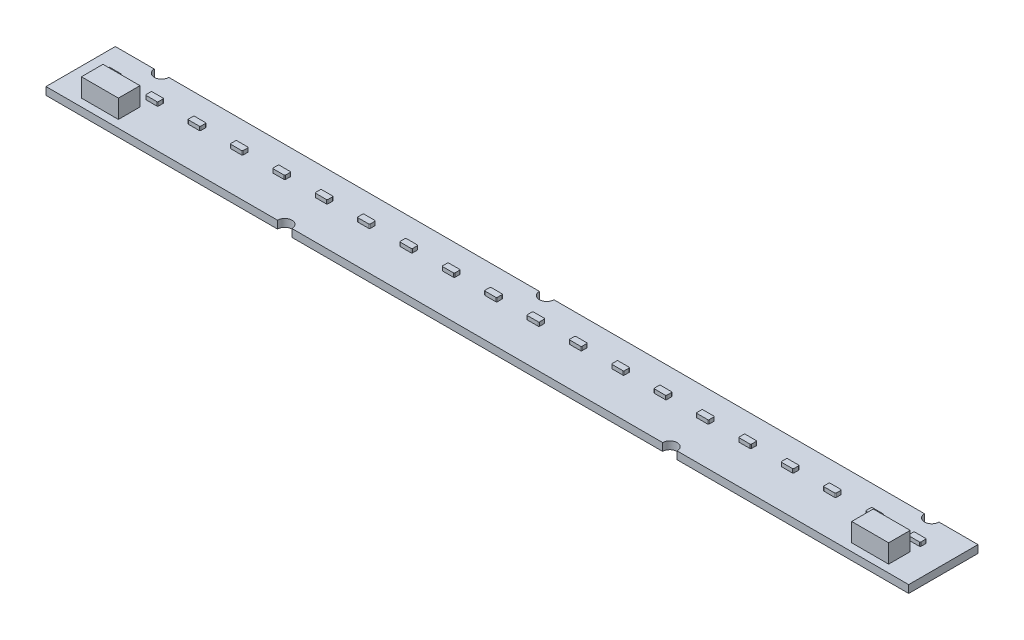
SolidWorks part; units mm, degrees
ref_plane "Alzado" through (0, 0, 0) normal (0, 0, 1) x (1, 0, 0)
ref_plane "Planta" through (0, 0, 0) normal (0, 1, 0) x (1, 0, 0)
ref_plane "Vista lateral" through (0, 0, 0) normal (1, 0, 0) x (0, 0, -1)
sketch "Croquis1" plane through (0, 0, 0) normal (0, 1, 0) x (1, 0, 0)
  line L0 (-140, 11.25) -> (140, -11.25) construction
  line L1 (-140, 11.25) -> (140, 11.25)
  line L2 (-140, 11.25) -> (-140, -11.25)
  line L3 (-140, -11.25) -> (140, -11.25)
  line L4 (140, 11.25) -> (140, -11.25)
  dimension "D1" = 22.5
  dimension "D2" = 280
extrude "Saliente-Extruir1" add sketch "Croquis1" along normal blind 2.5
sketch "Croquis2" plane through (0, 2.5, 0) normal (0, 1, 0) x (1, 0, 0)
  line L0 (140, 11.25) -> (-140, 11.25) construction
  line L1 (-127.35, 11.25) -> (-122.65, 11.25)
  line L2 (-140, 11.25) -> (-140, -11.25) construction
  line L3 (-140, -11.25) -> (140, -11.25) construction
  line L4 (-64.85, -11.25) -> (-60.15, -11.25)
  line L5 (60.15, -11.25) -> (64.85, -11.25)
  line L6 (-2.35, 11.25) -> (2.35, 11.25)
  line L7 (122.65, 11.25) -> (127.35, 11.25)
  arc A0 (-127.35, 11.25) -> (-122.65, 11.25) centre (-125, 11.25) ccw
  arc A1 (-60.15, -11.25) -> (-64.85, -11.25) centre (-62.5, -11.25) ccw
  arc A2 (64.85, -11.25) -> (60.15, -11.25) centre (62.5, -11.25) ccw
  arc A3 (-2.35, 11.25) -> (2.35, 11.25) centre (0, 11.25) ccw
  arc A4 (122.65, 11.25) -> (127.35, 11.25) centre (125, 11.25) ccw
  dimension "D1" = 2.35
  dimension "D2" = 15
  dimension "D3" = 62.5
  dimension "D4" = 2
  dimension "D5" = 3
extrude "Cortar-Extruir1" cut sketch "Croquis2" against normal up to next
sketch "Croquis3" plane through (0, 2.5, 0) normal (0, 1, 0) x (1, 0, 0)
  line L0 (-132, 3.25) -> (-132, 1.25) construction
  line L1 (-133.75, 3.25) -> (-130.25, 3.25)
  line L2 (-134, 3) -> (-134, 1.5)
  line L3 (-133.75, 1.25) -> (-130.25, 1.25)
  line L4 (-130, 3) -> (-130, 1.5)
  line L5 (-140, 11.25) -> (-140, -11.25) construction
  line L6 (-127.35, 11.25) -> (-140, 11.25) construction
  line L7 (-120, 1.25) -> (-116.5, 1.25)
  line L8 (-120.25, 3) -> (-120.25, 1.5)
  line L9 (-116.25, 3) -> (-116.25, 1.5)
  line L10 (-120, 3.25) -> (-116.5, 3.25)
  line L11 (-106.25, 1.25) -> (-102.75, 1.25)
  line L12 (-106.5, 3) -> (-106.5, 1.5)
  line L13 (-102.5, 3) -> (-102.5, 1.5)
  line L14 (-106.25, 3.25) -> (-102.75, 3.25)
  line L15 (-92.5, 1.25) -> (-89, 1.25)
  line L16 (-92.75, 3) -> (-92.75, 1.5)
  line L17 (-88.75, 3) -> (-88.75, 1.5)
  line L18 (-92.5, 3.25) -> (-89, 3.25)
  line L19 (-78.75, 1.25) -> (-75.25, 1.25)
  line L20 (-79, 3) -> (-79, 1.5)
  line L21 (-75, 3) -> (-75, 1.5)
  line L22 (-78.75, 3.25) -> (-75.25, 3.25)
  line L23 (-65, 1.25) -> (-61.5, 1.25)
  line L24 (-65.25, 3) -> (-65.25, 1.5)
  line L25 (-61.25, 3) -> (-61.25, 1.5)
  line L26 (-65, 3.25) -> (-61.5, 3.25)
  line L27 (-51.25, 1.25) -> (-47.75, 1.25)
  line L28 (-51.5, 3) -> (-51.5, 1.5)
  line L29 (-47.5, 3) -> (-47.5, 1.5)
  line L30 (-51.25, 3.25) -> (-47.75, 3.25)
  line L31 (-37.5, 1.25) -> (-34, 1.25)
  line L32 (-37.75, 3) -> (-37.75, 1.5)
  line L33 (-33.75, 3) -> (-33.75, 1.5)
  line L34 (-37.5, 3.25) -> (-34, 3.25)
  line L35 (-23.75, 1.25) -> (-20.25, 1.25)
  line L36 (-24, 3) -> (-24, 1.5)
  line L37 (-20, 3) -> (-20, 1.5)
  line L38 (-23.75, 3.25) -> (-20.25, 3.25)
  line L39 (-10, 1.25) -> (-6.5, 1.25)
  line L40 (-10.25, 3) -> (-10.25, 1.5)
  line L41 (-6.25, 3) -> (-6.25, 1.5)
  line L42 (-10, 3.25) -> (-6.5, 3.25)
  line L43 (3.75, 1.25) -> (7.25, 1.25)
  line L44 (3.5, 3) -> (3.5, 1.5)
  line L45 (7.5, 3) -> (7.5, 1.5)
  line L46 (3.75, 3.25) -> (7.25, 3.25)
  line L47 (17.5, 1.25) -> (21, 1.25)
  line L48 (17.25, 3) -> (17.25, 1.5)
  line L49 (21.25, 3) -> (21.25, 1.5)
  line L50 (17.5, 3.25) -> (21, 3.25)
  line L51 (31.25, 1.25) -> (34.75, 1.25)
  line L52 (31, 3) -> (31, 1.5)
  line L53 (35, 3) -> (35, 1.5)
  line L54 (31.25, 3.25) -> (34.75, 3.25)
  line L55 (45, 1.25) -> (48.5, 1.25)
  line L56 (44.75, 3) -> (44.75, 1.5)
  line L57 (48.75, 3) -> (48.75, 1.5)
  line L58 (45, 3.25) -> (48.5, 3.25)
  line L59 (58.75, 1.25) -> (62.25, 1.25)
  line L60 (58.5, 3) -> (58.5, 1.5)
  line L61 (62.5, 3) -> (62.5, 1.5)
  line L62 (58.75, 3.25) -> (62.25, 3.25)
  line L63 (72.5, 1.25) -> (76, 1.25)
  line L64 (72.25, 3) -> (72.25, 1.5)
  line L65 (76.25, 3) -> (76.25, 1.5)
  line L66 (72.5, 3.25) -> (76, 3.25)
  line L67 (86.25, 1.25) -> (89.75, 1.25)
  line L68 (86, 3) -> (86, 1.5)
  line L69 (90, 3) -> (90, 1.5)
  line L70 (86.25, 3.25) -> (89.75, 3.25)
  line L71 (100, 1.25) -> (103.5, 1.25)
  line L72 (99.75, 3) -> (99.75, 1.5)
  line L73 (103.75, 3) -> (103.75, 1.5)
  line L74 (100, 3.25) -> (103.5, 3.25)
  line L75 (113.75, 1.25) -> (117.25, 1.25)
  line L76 (113.5, 3) -> (113.5, 1.5)
  line L77 (117.5, 3) -> (117.5, 1.5)
  line L78 (113.75, 3.25) -> (117.25, 3.25)
  line L79 (127.5, 1.25) -> (131, 1.25)
  line L80 (127.25, 3) -> (127.25, 1.5)
  line L81 (131.25, 3) -> (131.25, 1.5)
  line L82 (127.5, 3.25) -> (131, 3.25)
  arc A0 (-130.25, 3.25) -> (-130, 3) centre (-130.25, 3) cw
  arc A1 (-130.25, 1.25) -> (-130, 1.5) centre (-130.25, 1.5) ccw
  arc A2 (-134, 1.5) -> (-133.75, 1.25) centre (-133.75, 1.5) ccw
  arc A3 (-133.75, 3.25) -> (-134, 3) centre (-133.75, 3) ccw
  arc A4 (-120.25, 1.5) -> (-120, 1.25) centre (-120, 1.5) ccw
  arc A5 (-116.5, 1.25) -> (-116.25, 1.5) centre (-116.5, 1.5) ccw
  arc A6 (-116.5, 3.25) -> (-116.25, 3) centre (-116.5, 3) cw
  arc A7 (-120, 3.25) -> (-120.25, 3) centre (-120, 3) ccw
  arc A8 (-106.5, 1.5) -> (-106.25, 1.25) centre (-106.25, 1.5) ccw
  arc A9 (-102.75, 1.25) -> (-102.5, 1.5) centre (-102.75, 1.5) ccw
  arc A10 (-102.75, 3.25) -> (-102.5, 3) centre (-102.75, 3) cw
  arc A11 (-106.25, 3.25) -> (-106.5, 3) centre (-106.25, 3) ccw
  arc A12 (-92.75, 1.5) -> (-92.5, 1.25) centre (-92.5, 1.5) ccw
  arc A13 (-89, 1.25) -> (-88.75, 1.5) centre (-89, 1.5) ccw
  arc A14 (-89, 3.25) -> (-88.75, 3) centre (-89, 3) cw
  arc A15 (-92.5, 3.25) -> (-92.75, 3) centre (-92.5, 3) ccw
  arc A16 (-79, 1.5) -> (-78.75, 1.25) centre (-78.75, 1.5) ccw
  arc A17 (-75.25, 1.25) -> (-75, 1.5) centre (-75.25, 1.5) ccw
  arc A18 (-75.25, 3.25) -> (-75, 3) centre (-75.25, 3) cw
  arc A19 (-78.75, 3.25) -> (-79, 3) centre (-78.75, 3) ccw
  arc A20 (-65.25, 1.5) -> (-65, 1.25) centre (-65, 1.5) ccw
  arc A21 (-61.5, 1.25) -> (-61.25, 1.5) centre (-61.5, 1.5) ccw
  arc A22 (-61.5, 3.25) -> (-61.25, 3) centre (-61.5, 3) cw
  arc A23 (-65, 3.25) -> (-65.25, 3) centre (-65, 3) ccw
  arc A24 (-51.5, 1.5) -> (-51.25, 1.25) centre (-51.25, 1.5) ccw
  arc A25 (-47.75, 1.25) -> (-47.5, 1.5) centre (-47.75, 1.5) ccw
  arc A26 (-47.75, 3.25) -> (-47.5, 3) centre (-47.75, 3) cw
  arc A27 (-51.25, 3.25) -> (-51.5, 3) centre (-51.25, 3) ccw
  arc A28 (-37.75, 1.5) -> (-37.5, 1.25) centre (-37.5, 1.5) ccw
  arc A29 (-34, 1.25) -> (-33.75, 1.5) centre (-34, 1.5) ccw
  arc A30 (-34, 3.25) -> (-33.75, 3) centre (-34, 3) cw
  arc A31 (-37.5, 3.25) -> (-37.75, 3) centre (-37.5, 3) ccw
  arc A32 (-24, 1.5) -> (-23.75, 1.25) centre (-23.75, 1.5) ccw
  arc A33 (-20.25, 1.25) -> (-20, 1.5) centre (-20.25, 1.5) ccw
  arc A34 (-20.25, 3.25) -> (-20, 3) centre (-20.25, 3) cw
  arc A35 (-23.75, 3.25) -> (-24, 3) centre (-23.75, 3) ccw
  arc A36 (-10.25, 1.5) -> (-10, 1.25) centre (-10, 1.5) ccw
  arc A37 (-6.5, 1.25) -> (-6.25, 1.5) centre (-6.5, 1.5) ccw
  arc A38 (-6.5, 3.25) -> (-6.25, 3) centre (-6.5, 3) cw
  arc A39 (-10, 3.25) -> (-10.25, 3) centre (-10, 3) ccw
  arc A40 (3.5, 1.5) -> (3.75, 1.25) centre (3.75, 1.5) ccw
  arc A41 (7.25, 1.25) -> (7.5, 1.5) centre (7.25, 1.5) ccw
  arc A42 (7.25, 3.25) -> (7.5, 3) centre (7.25, 3) cw
  arc A43 (3.75, 3.25) -> (3.5, 3) centre (3.75, 3) ccw
  arc A44 (17.25, 1.5) -> (17.5, 1.25) centre (17.5, 1.5) ccw
  arc A45 (21, 1.25) -> (21.25, 1.5) centre (21, 1.5) ccw
  arc A46 (21, 3.25) -> (21.25, 3) centre (21, 3) cw
  arc A47 (17.5, 3.25) -> (17.25, 3) centre (17.5, 3) ccw
  arc A48 (31, 1.5) -> (31.25, 1.25) centre (31.25, 1.5) ccw
  arc A49 (34.75, 1.25) -> (35, 1.5) centre (34.75, 1.5) ccw
  arc A50 (34.75, 3.25) -> (35, 3) centre (34.75, 3) cw
  arc A51 (31.25, 3.25) -> (31, 3) centre (31.25, 3) ccw
  arc A52 (44.75, 1.5) -> (45, 1.25) centre (45, 1.5) ccw
  arc A53 (48.5, 1.25) -> (48.75, 1.5) centre (48.5, 1.5) ccw
  arc A54 (48.5, 3.25) -> (48.75, 3) centre (48.5, 3) cw
  arc A55 (45, 3.25) -> (44.75, 3) centre (45, 3) ccw
  arc A56 (58.5, 1.5) -> (58.75, 1.25) centre (58.75, 1.5) ccw
  arc A57 (62.25, 1.25) -> (62.5, 1.5) centre (62.25, 1.5) ccw
  arc A58 (62.25, 3.25) -> (62.5, 3) centre (62.25, 3) cw
  arc A59 (58.75, 3.25) -> (58.5, 3) centre (58.75, 3) ccw
  arc A60 (72.25, 1.5) -> (72.5, 1.25) centre (72.5, 1.5) ccw
  arc A61 (76, 1.25) -> (76.25, 1.5) centre (76, 1.5) ccw
  arc A62 (76, 3.25) -> (76.25, 3) centre (76, 3) cw
  arc A63 (72.5, 3.25) -> (72.25, 3) centre (72.5, 3) ccw
  arc A64 (86, 1.5) -> (86.25, 1.25) centre (86.25, 1.5) ccw
  arc A65 (89.75, 1.25) -> (90, 1.5) centre (89.75, 1.5) ccw
  arc A66 (89.75, 3.25) -> (90, 3) centre (89.75, 3) cw
  arc A67 (86.25, 3.25) -> (86, 3) centre (86.25, 3) ccw
  arc A68 (99.75, 1.5) -> (100, 1.25) centre (100, 1.5) ccw
  arc A69 (103.5, 1.25) -> (103.75, 1.5) centre (103.5, 1.5) ccw
  arc A70 (103.5, 3.25) -> (103.75, 3) centre (103.5, 3) cw
  arc A71 (100, 3.25) -> (99.75, 3) centre (100, 3) ccw
  arc A72 (113.5, 1.5) -> (113.75, 1.25) centre (113.75, 1.5) ccw
  arc A73 (117.25, 1.25) -> (117.5, 1.5) centre (117.25, 1.5) ccw
  arc A74 (117.25, 3.25) -> (117.5, 3) centre (117.25, 3) cw
  arc A75 (113.75, 3.25) -> (113.5, 3) centre (113.75, 3) ccw
  arc A76 (127.25, 1.5) -> (127.5, 1.25) centre (127.5, 1.5) ccw
  arc A77 (131, 1.25) -> (131.25, 1.5) centre (131, 1.5) ccw
  arc A78 (131, 3.25) -> (131.25, 3) centre (131, 3) cw
  arc A79 (127.5, 3.25) -> (127.25, 3) centre (127.5, 3) ccw
  point P6 (-130, 3.25)
  point P11 (-134, 1.25)
  point P14 (-134, 3.25)
  point P17 (-132, 2.25)
  dimension "D3" = 0.25
  dimension "D1" = 2
  dimension "D2" = 4
  dimension "D4" = 8
  dimension "D5" = 8
  dimension "D6" = 20
extrude "Saliente-Extruir2" add sketch "Croquis3" along normal blind 1.25
sketch "Croquis4" plane through (0, 2.5, 0) normal (0, 1, 0) x (1, 0, 0)
  line L0 (-125, -1.75) -> (-125, -8.75) construction
  line L1 (-131, -1.75) -> (-119, -1.75)
  line L2 (-131, -1.75) -> (-131, -8.75)
  line L3 (-131, -8.75) -> (-119, -8.75)
  line L4 (-119, -1.75) -> (-119, -8.75)
  line L5 (-140, -11.25) -> (-64.85, -11.25) construction
  arc A0 (-127.35, 11.25) -> (-122.65, 11.25) centre (-125, 11.25) ccw construction
  point P6 (-125, 8.9)
  dimension "D1" = 12
  dimension "D2" = 7
  dimension "D3" = 2.5
extrude "Saliente-Extruir3" add sketch "Croquis4" along normal blind 6
mirror "Simetría1" about plane through (0, 0, 0) normal (1, 0, 0) of "Saliente-Extruir3"
